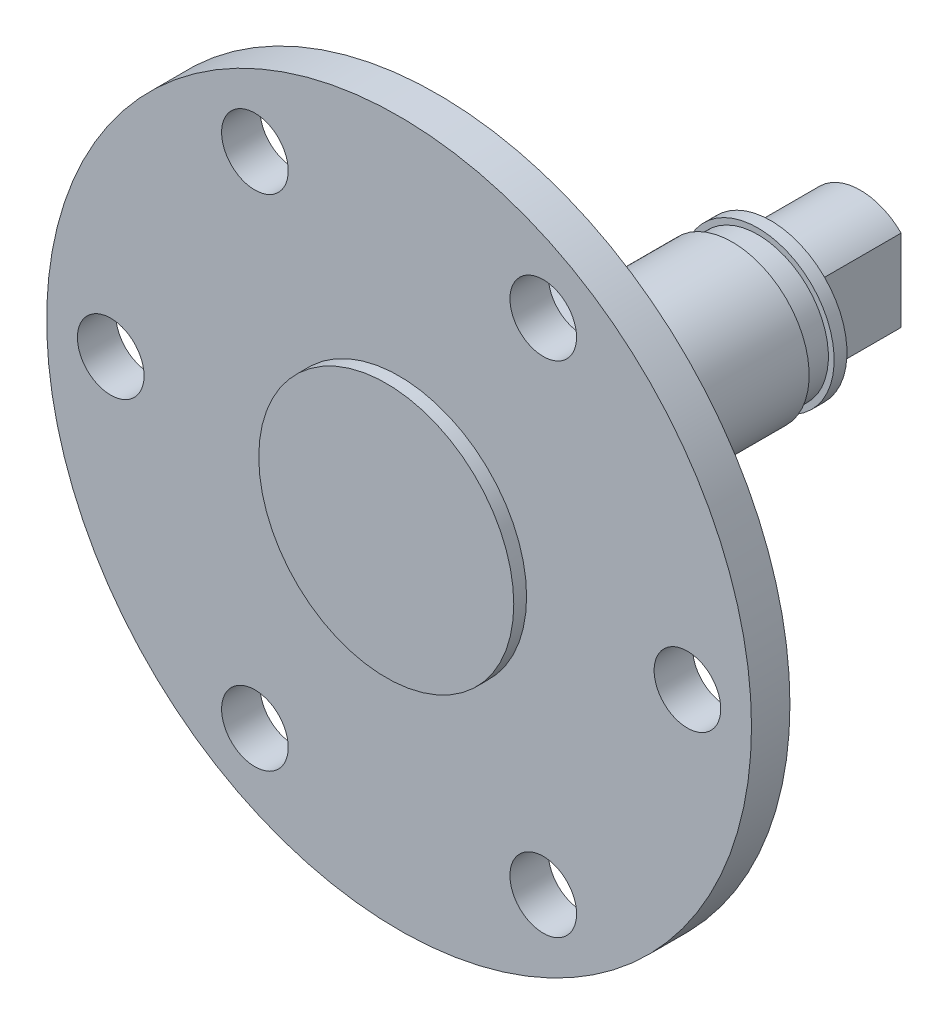
SolidWorks part; units mm, degrees
material "7075-O (SS)"
ref_plane "前视基准面" through (0, 0, 0) normal (0, 0, 1) x (1, 0, 0)
ref_plane "上视基准面" through (0, 0, 0) normal (0, 1, 0) x (1, 0, 0)
ref_plane "右视基准面" through (0, 0, 0) normal (1, 0, 0) x (0, 0, -1)
sketch "草图1" plane through (0, 0, 0) normal (0, 0, 1) x (1, 0, 0)
  circle A0 centre (0, 0) radius 27.5
  dimension "D1" = 55
extrude "凸台-拉伸1" add sketch "草图1" along normal blind 3
sketch "草图2" plane through (0, 0, 3) normal (0, 0, 1) x (1, 0, 0)
  circle A0 centre (0, 0) radius 22.5 construction
  circle A1 centre (22.5, 0) radius 2.6
  circle A2 centre (11.25, -19.4856) radius 2.6
  circle A3 centre (-11.25, -19.4856) radius 2.6
  circle A4 centre (-22.5, 0) radius 2.6
  circle A5 centre (-11.25, 19.4856) radius 2.6
  circle A6 centre (11.25, 19.4856) radius 2.6
  point P17 (0, 0)
  dimension "D1" = 45
  dimension "D2" = 5.2
  dimension "D3" = 6
extrude "切除-拉伸1" cut sketch "草图2" against normal blind 5
sketch "草图3" plane through (0, 0, 3) normal (0, 0, 1) x (1, 0, 0)
  circle A0 centre (0, 0) radius 9.95
  dimension "D1" = 19.9
extrude "凸台-拉伸2" add sketch "草图3" along normal blind 1
sketch "草图4" plane through (0, 0, 0) normal (0, 0, -1) x (-1, 0, 0)
  circle A0 centre (0, 0) radius 8
  dimension "D1" = 16
extrude "凸台-拉伸3" add sketch "草图4" along normal blind 13
sketch "草图5" plane through (0, 0, -13) normal (0, 0, -1) x (-1, 0, 0)
  circle A0 centre (0, 0) radius 6
  dimension "D1" = 12
extrude "凸台-拉伸4" add sketch "草图5" along normal blind 10
sketch "草图6" plane through (0, 0, -23) normal (0, 0, -1) x (-1, 0, 0)
  circle A0 centre (0, 0) radius 5.5
  dimension "D1" = 11
extrude "凸台-拉伸5" add sketch "草图6" along normal blind 2
sketch "草图7" plane through (0, 0, -25) normal (0, 0, -1) x (-1, 0, 0)
  circle A0 centre (0, 0) radius 5.95
  dimension "D1" = 11.9
extrude "凸台-拉伸6" add sketch "草图7" along normal blind 1
fillet "圆角1" radius 5 1 edges at (8, 0, 0)
sketch "草图8" plane through (0, 0, -26) normal (0, 0, -1) x (-1, 0, 0)
  line L1 (-3.175, -3.1889) -> (3.175, -3.1889)
  line L2 (-3.175, -3.1889) -> (-3.175, 3.1889)
  line L3 (-3.175, 3.1889) -> (3.175, 3.1889)
  line L4 (3.175, -3.1889) -> (3.175, 3.1889)
  line L5 (0, 3.1889) -> (0, -3.1889) construction
  line L6 (-3.175, 0) -> (3.175, 0) construction
  circle A0 centre (0, 0) radius 4.5
  dimension "D1" = 9
  dimension "D2" = 6.35
extrude "凸台-拉伸7" add sketch "草图8" along normal blind 7 contours L1 L4 L3 L2 | L1 A0 | L3 A0
sketch "草图9" [suppressed] plane through (0, 0, -26.1) normal (0, 0, -1) x (-1, 0, 0)
  line L0 (-4, 3) -> (-4, -3)
  arc A0 (-4, -3) -> (-4, 3) centre (0, 0) ccw
  dimension "D1" = 10
  dimension "D2" = 9
extrude "切除-拉伸2" [suppressed] cut sketch "草图9" against normal blind 10 contours A0 L0
sketch "草图10" plane through (0, 0, 3) normal (0, 0, 1) x (1, 0, 0)
  line L0 (0, 0) -> (11.25, -19.4856) construction
  arc A0 (9.2425, -24.0649) -> (16.2195, -20.0367) centre (11.25, -19.4856) ccw
  arc A1 (9.2425, -24.0649) -> (-9.2425, -24.0649) centre (0, -45.1484) ccw
  arc A2 (-16.2195, -20.0367) -> (-25.4621, -4.0282) centre (-39.0997, -22.5742) ccw
  arc A3 (-25.4621, 4.0282) -> (-16.2195, 20.0367) centre (-39.0997, 22.5742) ccw
  arc A4 (-9.2425, 24.0649) -> (9.2425, 24.0649) centre (0, 45.1484) ccw
  arc A5 (16.2195, 20.0367) -> (25.4621, 4.0282) centre (39.0997, 22.5742) ccw
  arc A6 (25.4621, -4.0282) -> (16.2195, -20.0367) centre (39.0997, -22.5742) ccw
  arc A7 (-16.2195, -20.0367) -> (-9.2425, -24.0649) centre (-11.25, -19.4856) ccw
  arc A8 (-25.4621, 4.0282) -> (-25.4621, -4.0282) centre (-22.5, 0) ccw
  arc A9 (-9.2425, 24.0649) -> (-16.2195, 20.0367) centre (-11.25, 19.4856) ccw
  arc A10 (16.2195, 20.0367) -> (9.2425, 24.0649) centre (11.25, 19.4856) ccw
  arc A11 (25.4621, -4.0282) -> (25.4621, 4.0282) centre (22.5, 0) ccw
  point P19 (0, 0)
  point P30 (0, 0)
  dimension "D1" = 45.1484
  dimension "D2" = 6
  dimension "D3" = 6
extrude "切除-拉伸4" [suppressed] cut sketch "草图10" against normal blind 10 flip side to cut
sketch "草图12" plane through (0, 0, 4) normal (0, 0, 1) x (1, 0, 0)
  circle A0 centre (0, 0) radius 4.5
  dimension "D1" = 9
extrude "切除-拉伸5" [suppressed] cut sketch "草图12" against normal blind 14
